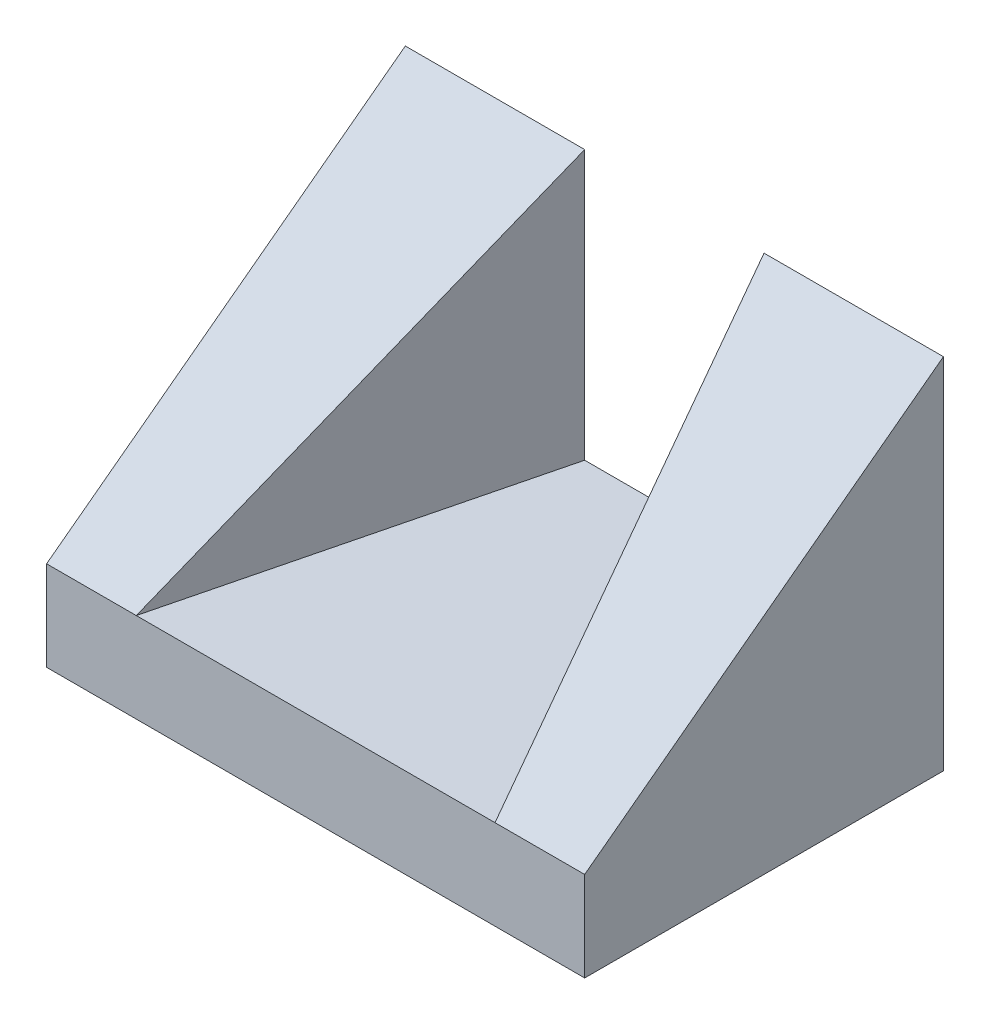
SolidWorks part; units mm, degrees
ref_plane "Front Plane" through (0, 0, 0) normal (0, 0, 1) x (1, 0, 0)
ref_plane "Top Plane" through (0, 0, 0) normal (0, 1, 0) x (1, 0, 0)
ref_plane "Right Plane" through (0, 0, 0) normal (1, 0, 0) x (0, 0, -1)
sketch "Sketch1" plane through (0, 0, 0) normal (1, 0, 0) x (0, 0, -1)
  line L0 (0, 0) -> (0, -40)
  line L1 (0, -40) -> (-40, -40)
  line L2 (-40, -40) -> (-40, -30)
  line L3 (-40, -30) -> (0, 0)
  dimension "D1" = 40
  dimension "D2" = 40
  dimension "D3" = 10
extrude "Boss-Extrude1" add sketch "Sketch1" along normal mid plane 60
sketch "Sketch2" plane through (0, 0, 0) normal (0, 1, 0) x (1, 0, 0)
  line L0 (0, 0) -> (0, -43.5477) construction
  line L1 (-10, 0) -> (10, 0)
  line L2 (30, 0) -> (-30, 0) construction
  line L3 (10, 0) -> (20, -40)
  line L4 (30, -40) -> (-30, -40) construction
  line L5 (20, -40) -> (-20, -40)
  line L6 (-10, 0) -> (-20, -40)
  point P11 (0, -40)
  dimension "D1" = 20
  dimension "D2" = 40
extrude "Cut-Extrude1" cut sketch "Sketch2" against normal blind 30
